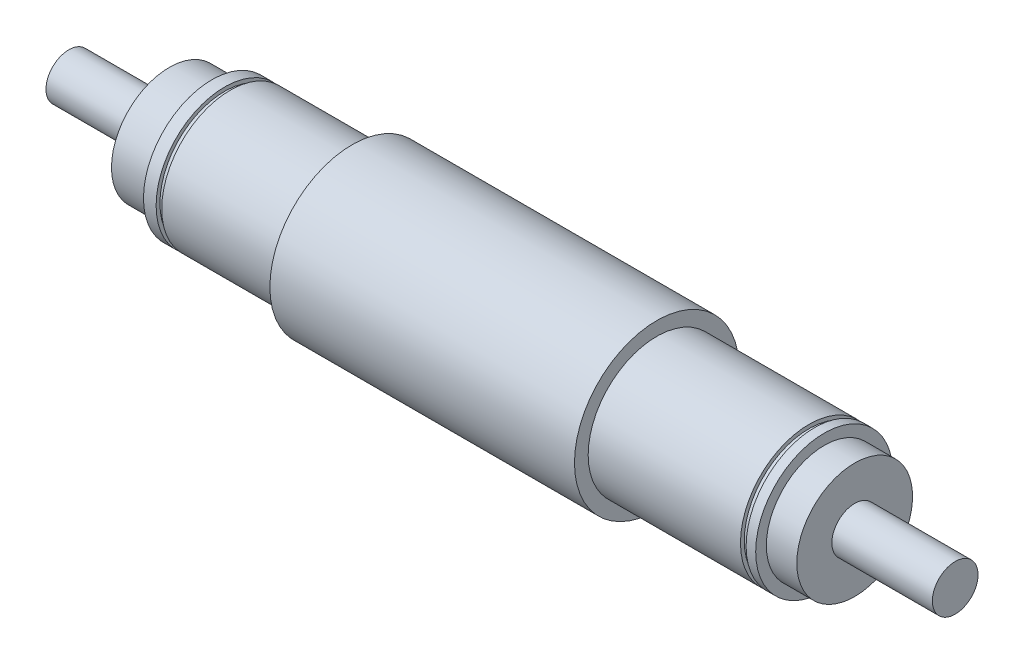
SolidWorks part; units mm, degrees
ref_plane "Piano frontale" through (0, 0, 0) normal (0, 0, 1) x (1, 0, 0)
ref_plane "Piano superiore" through (0, 0, 0) normal (0, 1, 0) x (1, 0, 0)
ref_plane "Piano destro" through (0, 0, 0) normal (1, 0, 0) x (0, 0, -1)
sketch "Schizzo1" plane through (0, 0, 0) normal (0, 0, 1) x (1, 0, 0)
  line L0 (0, 0) -> (291, 0)
  line L1 (0, 0) -> (0, 7.5)
  line L2 (0, 7.5) -> (33, 7.5)
  line L3 (33, 7.5) -> (33, 19)
  line L4 (33, 19) -> (47, 19)
  line L5 (47, 19) -> (47, 22.5)
  line L6 (47, 22.5) -> (93, 22.5)
  line L7 (93, 22.5) -> (93, 27)
  line L8 (93, 27) -> (193, 27)
  line L9 (193, 27) -> (193, 22.5)
  line L10 (193, 22.5) -> (248, 22.5)
  line L11 (248, 22.5) -> (248, 19)
  line L12 (248, 19) -> (258, 19)
  line L13 (258, 19) -> (258, 7.5)
  line L14 (258, 7.5) -> (291, 7.5)
  line L15 (291, 7.5) -> (291, 0)
  dimension "D1" = 291
  dimension "D2" = 33
  dimension "D3" = 47
  dimension "D4" = 93
  dimension "D5" = 7.5
  dimension "D6" = 19
  dimension "D7" = 22.5
  dimension "D8" = 27
  dimension "D9" = 98
  dimension "D10" = 43
  dimension "D11" = 33
revolve "Rivoluzione1" add sketch "Schizzo1" angle 360 about L0
sketch "Schizzo2" plane through (0, 0, 0) normal (0, 0, 1) x (1, 0, 0)
  line L0 (0, 0) -> (291, 0) construction
  line L1 (291, -7.5) -> (291, 7.5) construction
  line L2 (33, 7.5) -> (0, 7.5) construction
  line L3 (4.4, 7.5) -> (6, 7.5)
  line L4 (4.4, 7.5) -> (4.4, 14.3)
  line L5 (4.4, 14.3) -> (6, 14.3)
  line L6 (6, 7.5) -> (6, 14.3)
  line L7 (93, 22.5) -> (47, 22.5) construction
  line L8 (51.15, 22.5) -> (53, 22.5)
  line L9 (51.15, 22.5) -> (51.15, 21.25)
  line L10 (51.15, 21.25) -> (53, 21.25)
  line L11 (53, 22.5) -> (53, 21.25)
  line L12 (248, 22.5) -> (193, 22.5) construction
  line L13 (243, 22.5) -> (244.85, 22.5)
  line L14 (243, 22.5) -> (243, 21.25)
  line L15 (243, 21.25) -> (244.85, 21.25)
  line L16 (244.85, 22.5) -> (244.85, 21.25)
  line L17 (291, 7.5) -> (258, 7.5) construction
  line L18 (285, 7.5) -> (286.6, 7.5)
  line L19 (285, 7.5) -> (285, 14.3)
  line L20 (285, 14.3) -> (286.6, 14.3)
  line L21 (286.6, 7.5) -> (286.6, 14.3)
  line L22 (33, 7.5) -> (33, -7.5) construction
  line L23 (93, 27) -> (93, -27) construction
  line L24 (193, -27) -> (193, 27) construction
  line L25 (258, -19) -> (258, 19) construction
  point P31 (5.2, 14.3)
  dimension "D1" = 1.6
  dimension "D2" = 27
  dimension "D3" = 14.3
  dimension "D4" = 1.85
  dimension "D5" = 40
  dimension "D6" = 21.25
  dimension "D7" = 50
  dimension "D8" = 27
revolve "Taglia-Rivoluzione1" cut sketch "Schizzo2" angle 360 about L0
